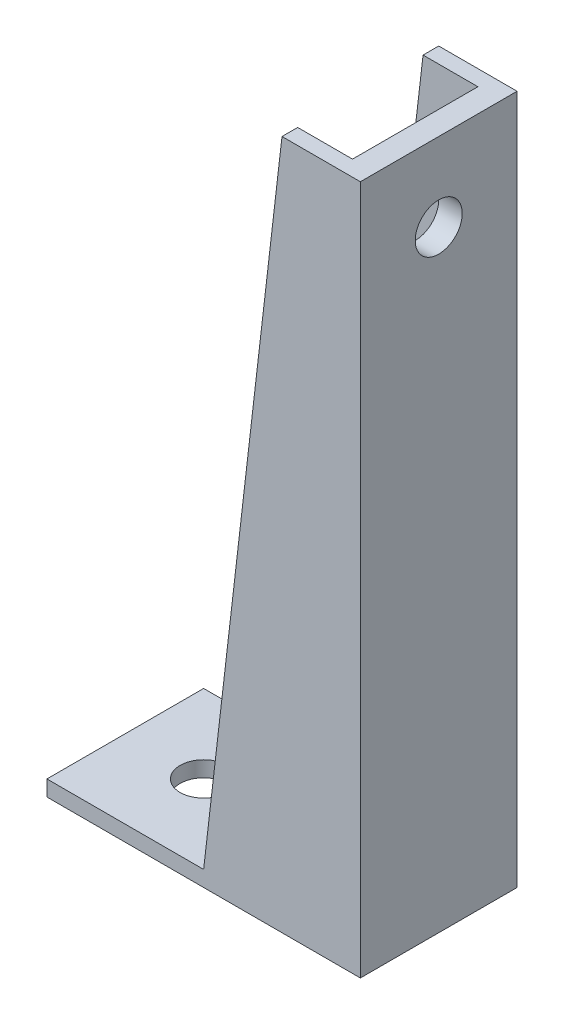
SolidWorks part; units mm, degrees
ref_plane "Front Plane" through (0, 0, 0) normal (0, 0, 1) x (1, 0, 0)
ref_plane "Top Plane" through (0, 0, 0) normal (0, 1, 0) x (1, 0, 0)
ref_plane "Right Plane" through (0, 0, 0) normal (1, 0, 0) x (0, 0, -1)
sketch "Sketch1" plane through (0, 0, 0) normal (0, 1, 0) x (1, 0, 0)
  line L1 (0, 0) -> (40, 0)
  line L2 (0, 0) -> (0, 20)
  line L3 (0, 20) -> (40, 20)
  line L4 (40, 0) -> (40, 20)
  dimension "D1" = 40
  dimension "D2" = 20
extrude "Boss-Extrude1" add sketch "Sketch1" along normal blind 2
sketch "Sketch2" plane through (0, 2, 0) normal (0, 1, 0) x (1, 0, 0)
  line L0 (0, 0) -> (40, 0) construction
  line L1 (0, 20) -> (0, 0) construction
  circle A0 centre (10, 10) radius 3
  dimension "D1" = 6
  dimension "D2" = 10
  dimension "D3" = 10
extrude "Cut-Extrude1" cut sketch "Sketch2" against normal blind 2
sketch "Sketch3" plane through (0, 2, 0) normal (0, 1, 0) x (1, 0, 0)
  line L0 (40, 20) -> (0, 20) construction
  line L1 (40, 0) -> (20, 0)
  line L2 (40, 0) -> (40, 20)
  line L3 (40, 20) -> (20, 20)
  line L4 (20, 0) -> (20, 20)
  line L6 (22, 2) -> (37, 2)
  line L7 (22, 2) -> (22, 18)
  line L8 (22, 18) -> (37, 18)
  line L9 (37, 2) -> (37, 18)
  dimension "D1" = 2
  dimension "D2" = 2
  dimension "D3" = 3
  dimension "D4" = 2
extrude "Boss-Extrude2" add sketch "Sketch3" along normal blind 86
sketch "Sketch4" plane through (40, 0, 0) normal (1, 0, 0) x (0, 0, -1)
  line L0 (0, 88) -> (20, 88) construction
  line L1 (20, 88) -> (20, 0) construction
  circle A0 centre (10, 78) radius 3
  dimension "D1" = 6
  dimension "D2" = 10
  dimension "D3" = 10
extrude "Cut-Extrude2" cut sketch "Sketch4" against normal blind 86
sketch "Sketch5" plane through (0, 0, 0) normal (0, 0, 1) x (1, 0, 0)
  line L0 (30, 88) -> (20, 2)
  line L1 (20, 88) -> (40, 88) construction
  line L2 (20, 2) -> (20, 88)
  line L3 (20, 88) -> (30, 88)
extrude "Cut-Extrude3" cut sketch "Sketch5" against normal blind 86
